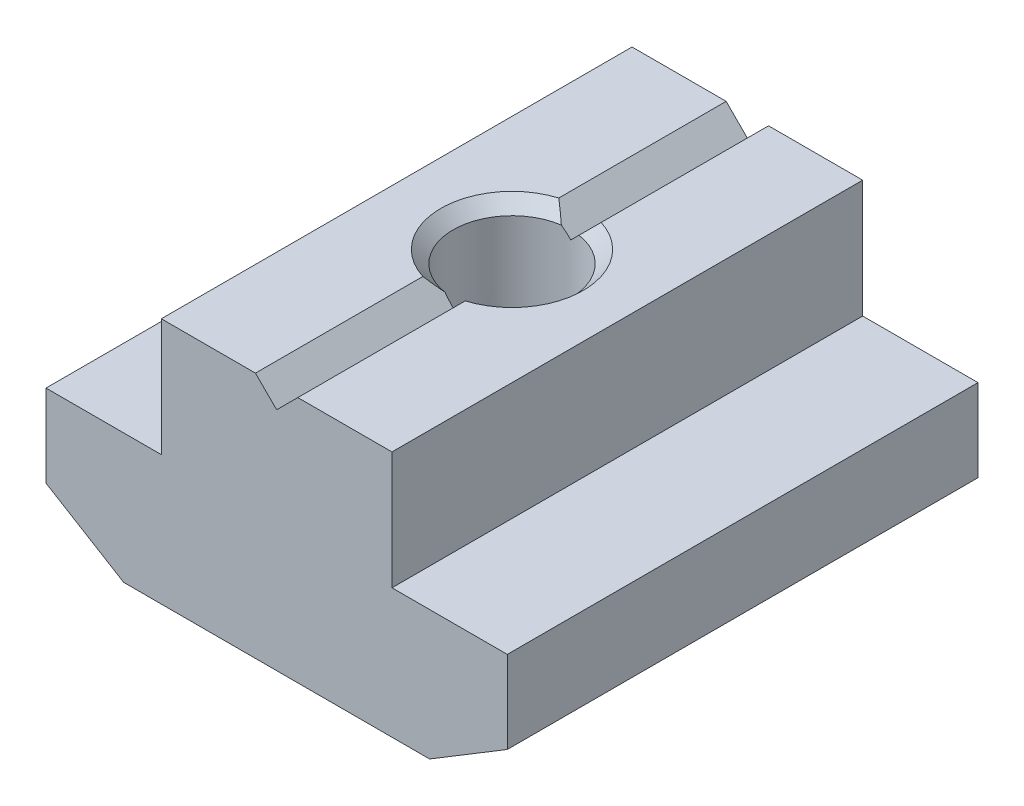
SolidWorks part; units mm, degrees
ref_plane "Front Plane" through (0, 0, 0) normal (0, 0, 1) x (1, 0, 0)
ref_plane "Top Plane" through (0, 0, 0) normal (0, 1, 0) x (1, 0, 0)
ref_plane "Right Plane" through (0, 0, 0) normal (1, 0, 0) x (0, 0, -1)
sketch "Sketch1" plane through (0, 0, 0) normal (0, 0, 1) x (1, 0, 0)
  line L0 (0, 10.5) -> (0, 0) construction
  line L1 (6.5, 0) -> (-6.5, 0)
  line L2 (-6.5, 0) -> (-9.8, 2)
  line L3 (-9.8, 2) -> (-9.8, 5.5)
  line L4 (-9.8, 5.5) -> (-4.9, 5.5)
  line L5 (-4.9, 5.5) -> (-4.9, 10.5)
  line L6 (-4.9, 10.5) -> (4.9, 10.5)
  line L7 (4.9, 5.5) -> (4.9, 10.5)
  line L8 (9.8, 5.5) -> (4.9, 5.5)
  line L9 (9.8, 2) -> (9.8, 5.5)
  line L10 (6.5, 0) -> (9.8, 2)
  point P4 (0, 0)
  dimension "D1" = 13
  dimension "D2" = 2
  dimension "D3" = 5.5
  dimension "D4" = 19.6
  dimension "D5" = 5
  dimension "D6" = 9.8
extrude "Boss-Extrude1" add sketch "Sketch1" against normal blind 20
sketch "Sketch2" plane through (0, 0, 0) normal (0, 0, 1) x (1, 0, 0)
  line L0 (0, 10.5) -> (0, 0) construction
  line L1 (4.9, 10.5) -> (-4.9, 10.5) construction
  line L2 (-0.9, 10.5) -> (0, 9.6)
  line L3 (0, 9.6) -> (0.9, 10.5)
  line L4 (-0.9, 10.5) -> (0.9, 10.5)
  dimension "D1" = 1.8
extrude "Cut-Extrude1" cut sketch "Sketch2" against normal blind 45
sketch "Sketch3" plane through (0, 10.5, 0) normal (0, 1, 0) x (1, 0, 0)
  line L0 (-4.9, 10) -> (4.9, 10) construction
  line L1 (-4.9, 20) -> (-4.9, 0) construction
  line L2 (4.9, 20) -> (4.9, 0) construction
  line L3 (0, 20) -> (0, 0) construction
sketch "Sketch6" plane through (0, 10.5, 0) normal (0, 1, 0) x (1, 0, 0)
  line L0 (-4.9, 10) -> (4.9, 10) construction
  point P0 (0, 10)
hole_wizard "M6x1.0 Tapped Hole1" positions "Sketch6" profile "Sketch5" tap size "M6x1.0" standard "ANSI Metric"
sketch "Sketch5" plane through (0, 10.5, -10) normal (1, 0, 0) x (0, 0, 1)
  line L0 (0, 0) -> (0, 16.5022)
  line L1 (0, 16.5022) -> (2.5, 15)
  line L2 (2.5, 15) -> (2.5, 0.525)
  line L3 (2.5, 0.525) -> (3.025, 0)
  line L5 (3.025, 0) -> (0, 0)
  line L6 (-2.5, 0.525) -> (-3.025, 0) construction
  line L10 (0, 16.5022) -> (-2.5, 15) construction
  line L11 (0, -6.35) -> (0, 107.95) construction
  dimension "Tap Drill Dia." = 5
  dimension "Tap Drill Depth" = 15
  dimension "Near C'Sink Dia." = 6.05
  dimension "Near C'Sink Angle" = 90
  dimension "Drill Angle" = 118
cosmetic thread "Hole Thread1" parameters "D1"=12, "D2"=6
